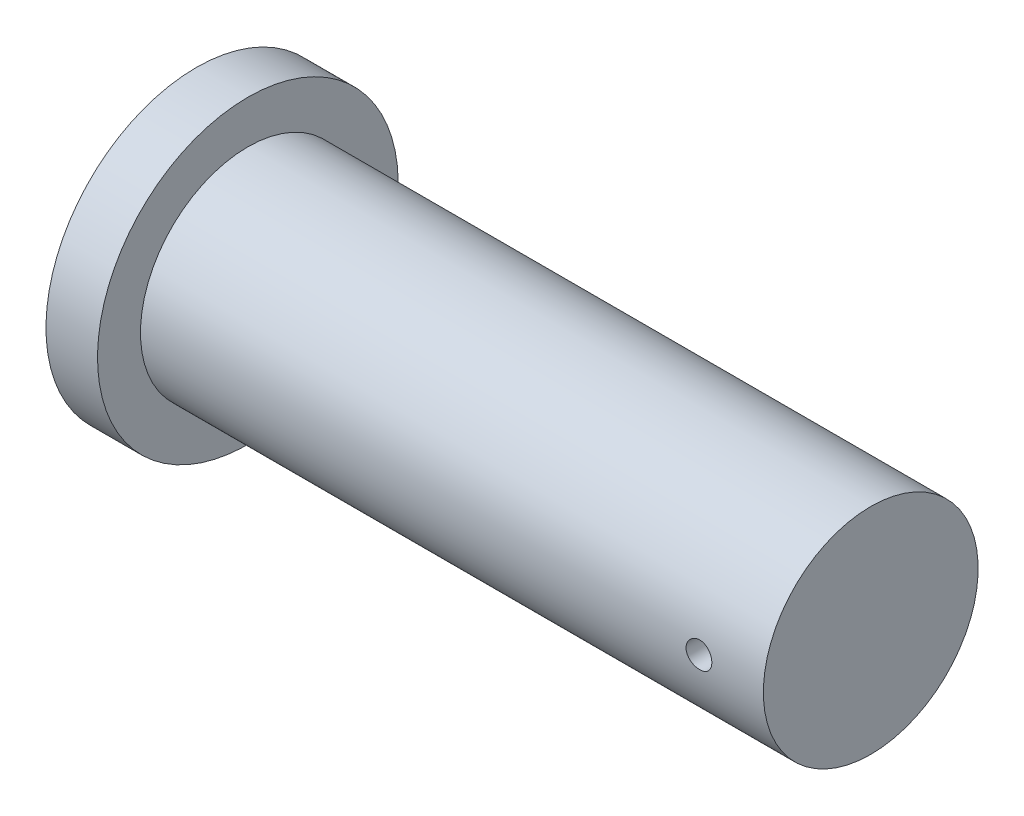
SolidWorks part; units mm, degrees
ref_plane "Front Plane" through (0, 0, 0) normal (0, 0, 1) x (1, 0, 0)
ref_plane "Top Plane" through (0, 0, 0) normal (0, 1, 0) x (1, 0, 0)
ref_plane "Right Plane" through (0, 0, 0) normal (1, 0, 0) x (0, 0, -1)
sketch "Sketch1" plane through (0, 0, 0) normal (0, 0, 1) x (1, 0, 0)
  line L0 (0, 0) -> (-1570, 0)
  line L1 (-1570, 0) -> (-1570, 350)
  line L2 (-1570, 350) -> (-1450, 350)
  line L3 (-1450, 350) -> (-1450, 250)
  line L4 (-1450, 250) -> (0, 250)
  line L5 (0, 250) -> (0, 0)
  dimension "D1" = 350
  dimension "D2" = 250
  dimension "D3" = 1570
  dimension "D4" = 120
revolve "Revolve1" add sketch "Sketch1" angle 360 about L0
sketch "Sketch3" plane through (0, 0, 0) normal (0, 0, 1) x (1, 0, 0)
  line L0 (-1450, -350) -> (-1450, 350) construction
  circle A0 centre (-150, 0) radius 30
  dimension "D1" = 60
  dimension "D2" = 1300
extrude "Cut-Extrude1" cut sketch "Sketch3" against normal mid plane 857
